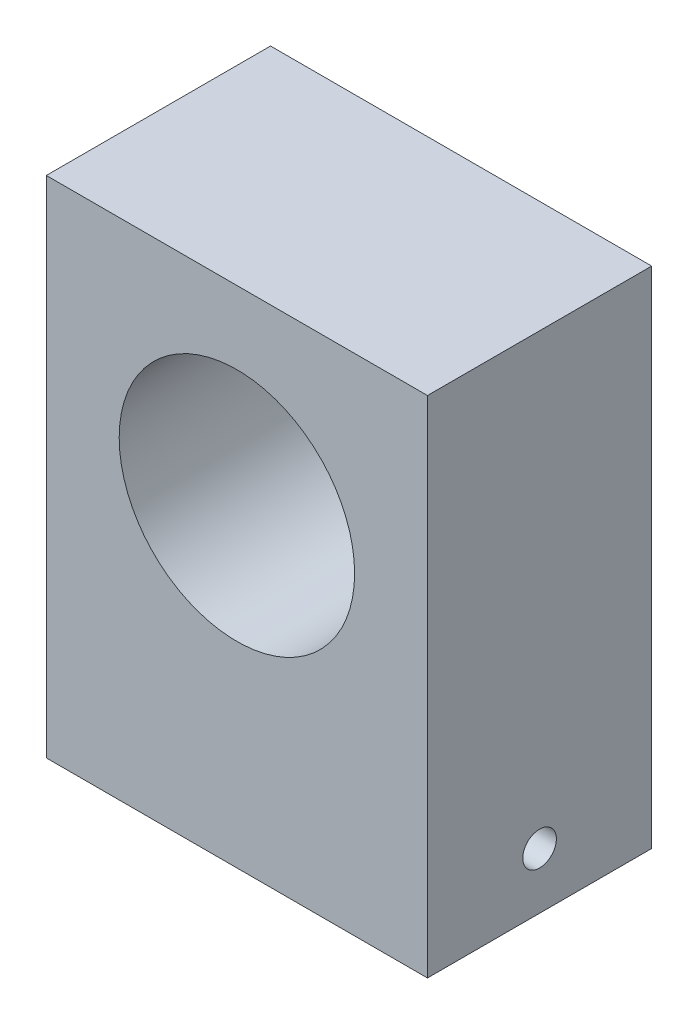
SolidWorks part; units mm, degrees
ref_plane "前视基准面" through (0, 0, 0) normal (0, 0, 1) x (1, 0, 0)
ref_plane "上视基准面" through (0, 0, 0) normal (0, 1, 0) x (1, 0, 0)
ref_plane "右视基准面" through (0, 0, 0) normal (1, 0, 0) x (0, 0, -1)
sketch "草图3" plane through (0, 0, 0) normal (0, 0, 1) x (1, 0, 0)
  line L0 (17, 45) -> (17, -14.655) construction
  line L1 (0, 0) -> (34, 0)
  line L2 (0, 0) -> (0, 45)
  line L3 (0, 45) -> (34, 45)
  line L4 (34, 0) -> (34, 45)
  dimension "D1" = 45
  dimension "D2" = 34
extrude "凸台-拉伸1" add sketch "草图3" against normal blind 20
sketch "草图4" plane through (0, 0, 0) normal (0, 0, 1) x (1, 0, 0)
  line L0 (17, 45) -> (17, 0) construction
  line L1 (34, 45) -> (0, 45) construction
  line L2 (0, 0) -> (34, 0) construction
  circle A0 centre (17, 28) radius 10.5
  dimension "D1" = 21
  dimension "D2" = 17
extrude "切除-拉伸1" cut sketch "草图4" against normal through all contours A0
sketch "草图7" plane through (0, 0, -20) normal (0, 0, -1) x (-1, 0, 0)
  line L0 (-17, 0) -> (-17, 18.6282) construction
  line L1 (0, 0) -> (-34, 0) construction
  line L3 (-24.65, 12) -> (-9.35, 12)
  line L4 (-24.65, 12) -> (-24.65, 0)
  line L5 (-24.65, 0) -> (-9.35, 0)
  line L6 (-9.35, 12) -> (-9.35, 0)
  line L7 (-24.65, 12) -> (-9.35, 0) construction
  line L8 (-24.65, 0) -> (-9.35, 12) construction
  point P4 (-17, 6)
  dimension "D1" = 15.3
  dimension "D2" = 12
extrude "切除-拉伸2" cut sketch "草图7" against normal blind 14 contours L4 L3 L6 L5
ref_plane "基准面1" through (24.65, 0, -20) normal (0, -1, 0) x (-1, 0, 0)
sketch "草图9" plane through (34, 0, 0) normal (1, 0, 0) x (0, 0, -1)
  line L0 (10, 0) -> (10, 18.8454) construction
  line L1 (20, 0) -> (0, 0) construction
  circle A0 centre (10, 5) radius 1.5
  dimension "D2" = 3
  dimension "D1" = 5
extrude "切除-拉伸3" cut sketch "草图9" against normal through all contours A0
